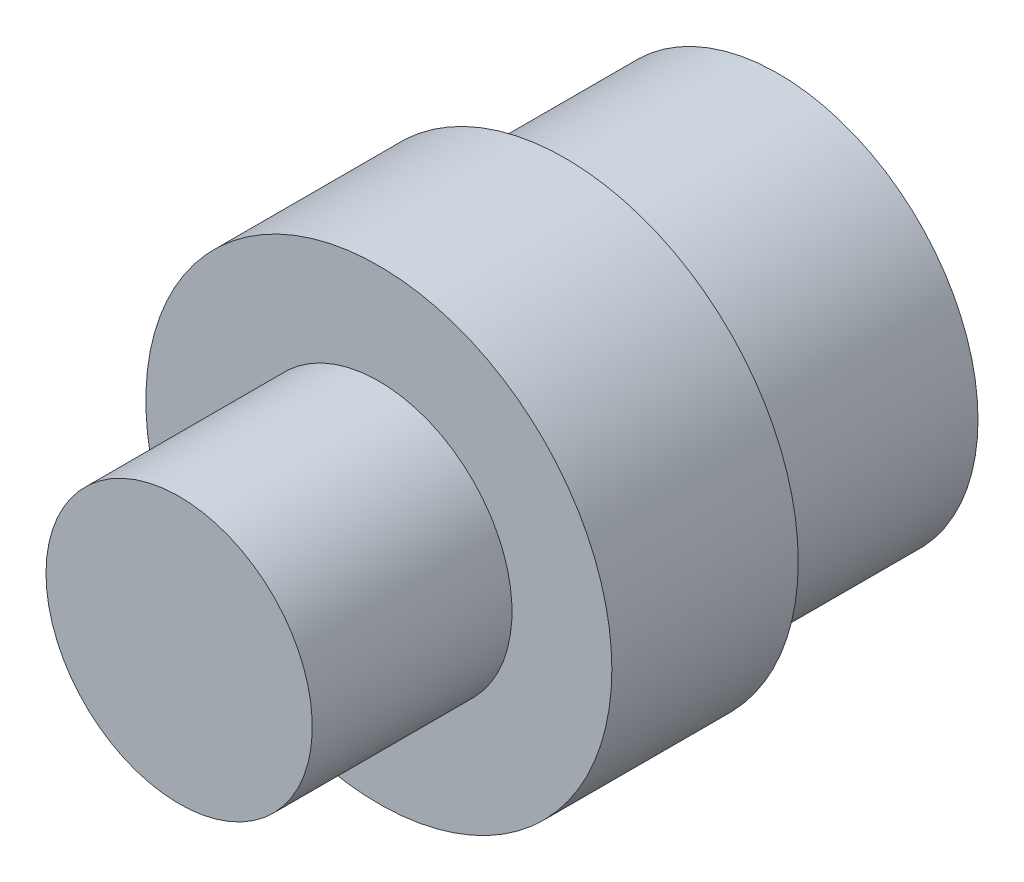
SolidWorks part; units mm, degrees
ref_plane "Front" through (0, 0, 0) normal (0, 0, 1) x (1, 0, 0)
ref_plane "Top" through (0, 0, 0) normal (0, 1, 0) x (1, 0, 0)
ref_plane "Right" through (0, 0, 0) normal (1, 0, 0) x (0, 0, -1)
sketch "Sketch1" plane through (0, 0, 0) normal (0, 0, 1) x (1, 0, 0)
  circle A0 centre (0, 0) radius 6.35
  dimension "D1" = 12.7
extrude "Extrude1" add sketch "Sketch1" along normal blind 9.525
sketch "Sketch2" plane through (0, 0, 0) normal (0, 0, -1) x (-1, 0, 0)
  circle A0 centre (0, 0) radius 9.525
  dimension "D1" = 19.05
extrude "Extrude2" add sketch "Sketch2" along normal blind 19.05
sketch "Sketch3" plane through (0, 0, 0) normal (0, 0, 1) x (1, 0, 0)
  circle A0 centre (0, 0) radius 11.1125
  dimension "D1" = 22.225
extrude "Extrude3" add sketch "Sketch3" against normal blind 8.89
